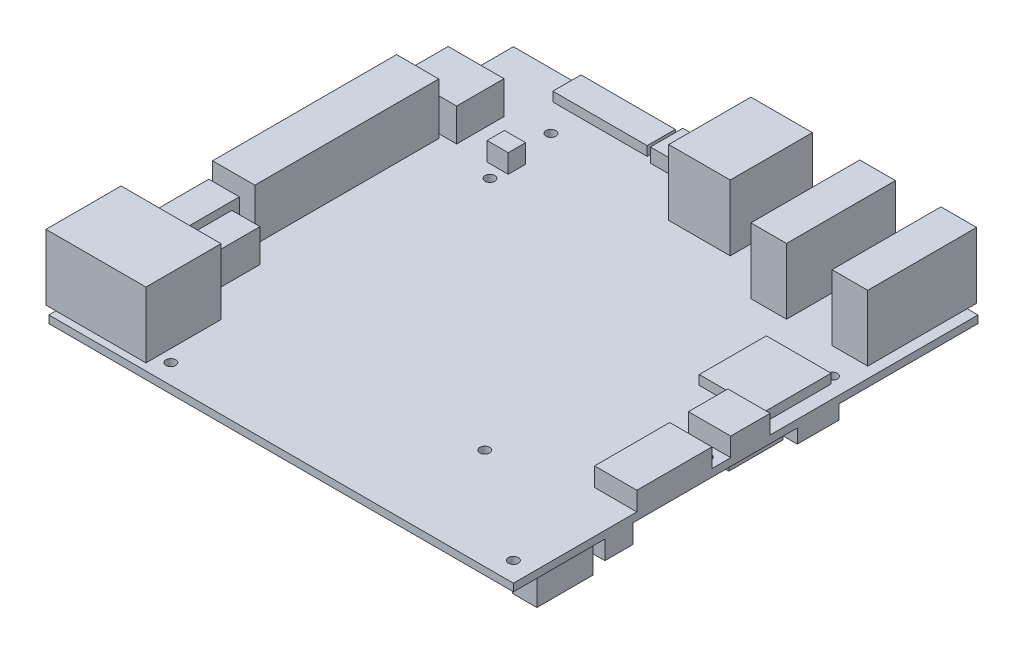
SolidWorks part; units mm, degrees
ref_plane "前视基准面" through (0, 0, 0) normal (0, 0, 1) x (1, 0, 0)
ref_plane "上视基准面" through (0, 0, 0) normal (0, 1, 0) x (1, 0, 0)
ref_plane "右视基准面" through (0, 0, 0) normal (1, 0, 0) x (0, 0, -1)
sketch "草图1" plane through (0, 0, 0) normal (0, 1, 0) x (1, 0, 0)
  line L1 (0, 0) -> (99, 0)
  line L2 (0, 0) -> (0, -99)
  line L3 (0, -99) -> (99, -99)
  line L4 (99, 0) -> (99, -99)
  line L5 (21.8, -26.8) -> (94.8, -26.8) construction
  line L6 (21.8, -26.8) -> (21.8, -94.8) construction
  line L7 (21.8, -94.8) -> (94.8, -94.8) construction
  line L8 (94.8, -26.8) -> (94.8, -94.8) construction
  circle A0 centre (21.8, -26.8) radius 1.05
  circle A1 centre (94.8, -26.8) radius 1.05
  circle A2 centre (21.8, -94.8) radius 1.05
  circle A3 centre (94.8, -94.8) radius 1.05
  circle A4 centre (8.7, -65.7) radius 1.05
  circle A5 centre (81.9, -4.6) radius 1.05
  circle A6 centre (96.3, -55.2) radius 1.05
  circle A7 centre (20, -12) radius 1.05
  circle A8 centre (71.4, -77.5) radius 1.05
  dimension "D7" = 2.1
  dimension "D8" = 2.1
  dimension "D9" = 2.1
  dimension "D10" = 2.1
  dimension "D21" = 2.1
  dimension "D22" = 2.1
  dimension "D23" = 2.1
  dimension "D24" = 2.1
  dimension "D25" = 2.1
  dimension "D1" = 99
  dimension "D2" = 99
  dimension "D3" = 21.8
  dimension "D4" = 4.2
  dimension "D5" = 68
  dimension "D6" = 73
  dimension "D11" = 8.7
  dimension "D12" = 33.3
  dimension "D13" = 81.9
  dimension "D14" = 94.4
  dimension "D15" = 96.3
  dimension "D16" = 43.8
  dimension "D17" = 20
  dimension "D18" = 87
  dimension "D19" = 71.4
  dimension "D20" = 21.5
extrude "凸台-拉伸1" add sketch "草图1" along normal blind 1.6
sketch "草图2" plane through (0, 1.6, 0) normal (0, 1, 0) x (1, 0, 0)
  line L0 (0, 0) -> (0, -99) construction
  line L5 (0, -99) -> (99, -99) construction
  line L18 (99, -99) -> (99, 0) construction
  line L19 (96.7, 2) -> (89.1, 2)
  line L20 (96.7, 2) -> (96.7, -21.2)
  line L21 (96.7, -21.2) -> (89.1, -21.2)
  line L22 (89.1, 2) -> (89.1, -21.2)
  line L23 (79.4, 2) -> (71.8, 2)
  line L24 (79.4, 2) -> (79.4, -21.2)
  line L25 (79.4, -21.2) -> (71.8, -21.2)
  line L26 (71.8, 2) -> (71.8, -21.2)
  line L27 (61.7, 2) -> (48.6, 2)
  line L28 (61.7, 2) -> (61.7, -15.5)
  line L29 (61.7, -15.5) -> (48.6, -15.5)
  line L30 (48.6, 2) -> (48.6, -15.5)
  line L31 (-2.1, -97.5) -> (19.2, -97.5)
  line L32 (-2.1, -97.5) -> (-2.1, -81.5)
  line L33 (-2.1, -81.5) -> (19.2, -81.5)
  line L34 (19.2, -97.5) -> (19.2, -81.5)
  line L35 (99, 0) -> (0, 0) construction
  dimension "D1" = 2.3
  dimension "D2" = 21.2
  dimension "D3" = 7.6
  dimension "D4" = 23.2
  dimension "D5" = 9.7
  dimension "D6" = 7.6
  dimension "D7" = 37.3
  dimension "D8" = 15.5
  dimension "D9" = 13.1
  dimension "D10" = 17.5
  dimension "D11" = 19.2
  dimension "D12" = 1.5
  dimension "D13" = 21.3
  dimension "D14" = 16
extrude "凸台-拉伸2" add sketch "草图2" along normal blind 14
sketch "草图3" plane through (0, 1.6, 0) normal (0, 1, 0) x (1, 0, 0)
  line L0 (48.6, 0) -> (0, 0) construction
  line L1 (44.7, 0) -> (36.1, 0)
  line L2 (44.7, 0) -> (44.7, -6.9)
  line L3 (44.7, -6.9) -> (36.1, -6.9)
  line L4 (36.1, 0) -> (36.1, -6.9)
  line L5 (0, 0) -> (0, -81.5) construction
  dimension "D1" = 36.1
  dimension "D2" = 6.9
  dimension "D3" = 8.6
extrude "凸台-拉伸3" add sketch "草图3" along normal blind 3
sketch "草图4" plane through (0, 1.6, 0) normal (0, 1, 0) x (1, 0, 0)
  line L0 (36.1, 0) -> (0, 0) construction
  line L1 (14.4, 0) -> (34.5, 0)
  line L2 (14.4, 0) -> (14.4, -6)
  line L3 (14.4, -6) -> (34.5, -6)
  line L4 (34.5, 0) -> (34.5, -6)
  line L5 (99, -99) -> (99, 0) construction
  line L6 (96.1, -28.4) -> (82.3, -28.4)
  line L7 (96.1, -28.4) -> (96.1, -42.7)
  line L8 (96.1, -42.7) -> (82.3, -42.7)
  line L9 (82.3, -28.4) -> (82.3, -42.7)
  line L10 (0, 0) -> (0, -81.5) construction
  line L11 (99, 0) -> (96.7, 0) construction
  dimension "D1" = 14.4
  dimension "D2" = 6
  dimension "D3" = 20.1
  dimension "D4" = 28.4
  dimension "D5" = 16.7
  dimension "D6" = 13.8
  dimension "D7" = 14.3
extrude "凸台-拉伸4" add sketch "草图4" along normal blind 2
sketch "草图5" plane through (0, 1.6, 0) normal (0, 1, 0) x (1, 0, 0)
  line L0 (0, 0) -> (0, -81.5) construction
  line L1 (0, -13.9) -> (11.9, -13.9)
  line L2 (0, -13.9) -> (0, -24)
  line L3 (0, -24) -> (11.9, -24)
  line L4 (11.9, -13.9) -> (11.9, -24)
  line L5 (14.4, 0) -> (0, 0) construction
  line L6 (0, -99) -> (99, -99) construction
  line L7 (7.2, -80.2) -> (13.2, -80.2)
  line L8 (7.2, -80.2) -> (7.2, -67.2)
  line L9 (7.2, -67.2) -> (13.2, -67.2)
  line L10 (13.2, -80.2) -> (13.2, -67.2)
  dimension "D1" = 13.9
  dimension "D2" = 11.9
  dimension "D3" = 10.1
  dimension "D4" = 18.8
  dimension "D5" = 7.2
  dimension "D6" = 6
  dimension "D7" = 13
extrude "凸台-拉伸5" add sketch "草图5" along normal blind 7
sketch "草图6" plane through (0, 1.6, 0) normal (0, 1, 0) x (1, 0, 0)
  line L0 (0, -24) -> (0, -81.5) construction
  line L1 (0, -64.1) -> (9, -64.1)
  line L2 (0, -64.1) -> (0, -24.9)
  line L3 (0, -24.9) -> (9, -24.9)
  line L4 (9, -64.1) -> (9, -24.9)
  line L5 (0, -99) -> (99, -99) construction
  dimension "D1" = 34.9
  dimension "D2" = 9
  dimension "D3" = 39.2
extrude "凸台-拉伸6" add sketch "草图6" along normal blind 11
sketch "草图7" plane through (0, 1.6, 0) normal (0, 1, 0) x (1, 0, 0)
  line L0 (0, -64.1) -> (0, -81.5) construction
  line L1 (0, -80.9) -> (6.5, -80.9)
  line L2 (0, -80.9) -> (0, -64.9)
  line L3 (0, -64.9) -> (6.5, -64.9)
  line L4 (6.5, -80.9) -> (6.5, -64.9)
  line L5 (0, -99) -> (99, -99) construction
  dimension "D1" = 18.1
  dimension "D2" = 6.5
  dimension "D3" = 16
extrude "凸台-拉伸7" add sketch "草图7" along normal blind 8
sketch "草图8" plane through (0, 1.6, 0) normal (0, 1, 0) x (1, 0, 0)
  line L0 (99, -99) -> (99, 0) construction
  line L1 (99, -72.7) -> (90, -72.7)
  line L2 (99, -72.7) -> (99, -56.7)
  line L3 (99, -56.7) -> (90, -56.7)
  line L4 (90, -72.7) -> (90, -56.7)
  line L5 (0, -99) -> (99, -99) construction
  line L6 (0, 0) -> (0, -13.9) construction
  line L7 (90, -52.7) -> (99, -52.7)
  line L8 (90, -52.7) -> (90, -44.3)
  line L9 (90, -44.3) -> (99, -44.3)
  line L10 (99, -52.7) -> (99, -44.3)
  line L11 (18.5, -20.4) -> (23, -20.4)
  line L12 (18.5, -20.4) -> (18.5, -24.1)
  line L13 (18.5, -24.1) -> (23, -24.1)
  line L14 (23, -20.4) -> (23, -24.1)
  line L15 (14.4, 0) -> (0, 0) construction
  dimension "D1" = 9
  dimension "D2" = 26.3
  dimension "D3" = 16
  dimension "D4" = 4
  dimension "D5" = 8.4
  dimension "D6" = 18.5
  dimension "D7" = 20.4
  dimension "D8" = 4.5
  dimension "D9" = 3.7
extrude "凸台-拉伸8" add sketch "草图8" along normal blind 4
sketch "草图9" plane through (0, 0, 0) normal (0, -1, 0) x (1, 0, 0)
  line L0 (99, 99) -> (99, 0) construction
  line L1 (98.4, 93.4) -> (93.2, 93.4)
  line L2 (98.4, 93.4) -> (98.4, 81.4)
  line L3 (98.4, 81.4) -> (93.2, 81.4)
  line L4 (93.2, 93.4) -> (93.2, 81.4)
  line L5 (0, 99) -> (99, 99) construction
  dimension "D1" = 0.6
  dimension "D2" = 5.6
  dimension "D3" = 5.2
  dimension "D4" = 12
extrude "凸台-拉伸9" add sketch "草图9" along normal blind 6
sketch "草图10" plane through (0, 0, 0) normal (0, -1, 0) x (1, 0, 0)
  line L0 (99, 99) -> (99, 0) construction
  line L1 (84.4, 73.5) -> (99, 73.5)
  line L2 (84.4, 73.5) -> (84.4, 79.5)
  line L3 (84.4, 79.5) -> (99, 79.5)
  line L4 (99, 73.5) -> (99, 79.5)
  line L5 (0, 99) -> (99, 99) construction
  circle A0 centre (85.4, 55.4) radius 7.5
  dimension "D6" = 15
  dimension "D1" = 19.5
  dimension "D2" = 14.6
  dimension "D3" = 6
  dimension "D4" = 13.6
  dimension "D5" = 43.6
extrude "凸台-拉伸10" add sketch "草图10" along normal blind 4
sketch "草图11" plane through (0, 0, 0) normal (0, -1, 0) x (1, 0, 0)
  line L0 (99, 73.5) -> (99, 0) construction
  line L1 (97.7, 51.8) -> (93.7, 51.8)
  line L2 (97.7, 51.8) -> (97.7, 40.2)
  line L3 (97.7, 40.2) -> (93.7, 40.2)
  line L4 (93.7, 51.8) -> (93.7, 40.2)
  line L5 (96.7, 0) -> (89.1, 0) construction
  line L6 (99, 0) -> (0, 0) construction
  line L7 (18.2, 0) -> (34.4, 0)
  line L8 (18.2, 0) -> (18.2, 6)
  line L9 (18.2, 6) -> (34.4, 6)
  line L10 (34.4, 0) -> (34.4, 6)
  line L11 (0, 0) -> (0, 99) construction
  dimension "D1" = 1.3
  dimension "D2" = 40.2
  dimension "D3" = 4
  dimension "D4" = 11.6
  dimension "D5" = 18.2
  dimension "D6" = 6
  dimension "D7" = 16.2
extrude "凸台-拉伸11" add sketch "草图11" along normal blind 2
sketch "草图12" plane through (0, 0, 0) normal (0, -1, 0) x (1, 0, 0)
  line L0 (99, 73.5) -> (99, 0) construction
  line L1 (99, 38.5) -> (91.5, 38.5)
  line L2 (99, 38.5) -> (99, 29.6)
  line L3 (99, 29.6) -> (91.5, 29.6)
  line L4 (91.5, 38.5) -> (91.5, 29.6)
  line L5 (99, 0) -> (34.4, 0) construction
  line L6 (36.1, 43.4) -> (39.6, 43.4)
  line L7 (36.1, 43.4) -> (36.1, 34.3)
  line L8 (36.1, 34.3) -> (39.6, 34.3)
  line L9 (39.6, 43.4) -> (39.6, 34.3)
  dimension "D1" = 29.6
  dimension "D2" = 7.5
  dimension "D3" = 8.9
  dimension "D4" = 59.4
  dimension "D5" = 34.3
  dimension "D6" = 3.5
  dimension "D7" = 9.1
extrude "凸台-拉伸12" add sketch "草图12" along normal blind 3
sketch "草图13" plane through (0, 0, 0) normal (0, -1, 0) x (1, 0, 0)
  line L0 (0, 0) -> (0, 99) construction
  line L1 (38, 88.4) -> (45.4, 88.4)
  line L2 (38, 88.4) -> (38, 66.5)
  line L3 (38, 66.5) -> (45.4, 66.5)
  line L4 (45.4, 88.4) -> (45.4, 66.5)
  line L5 (12.8, 66.2) -> (19.7, 66.2)
  line L6 (12.8, 66.2) -> (12.8, 44.3)
  line L7 (12.8, 44.3) -> (19.7, 44.3)
  line L8 (19.7, 66.2) -> (19.7, 44.3)
  line L9 (0, 99) -> (99, 99) construction
  dimension "D1" = 38
  dimension "D2" = 10.6
  dimension "D3" = 7.4
  dimension "D4" = 21.9
  dimension "D5" = 12.8
  dimension "D6" = 32.8
  dimension "D7" = 21.9
  dimension "D8" = 6.9
extrude "凸台-拉伸13" add sketch "草图13" along normal blind 6.4
sketch "草图14" plane through (0, 0, 0) normal (0, -1, 0) x (1, 0, 0)
  line L0 (0, 0) -> (0, 99) construction
  line L1 (99, 0) -> (34.4, 0) construction
  circle A0 centre (50, 36.3) radius 7.5
  dimension "D3" = 15
  dimension "D1" = 50
  dimension "D2" = 36.3
extrude "凸台-拉伸14" add sketch "草图14" along normal blind 8
